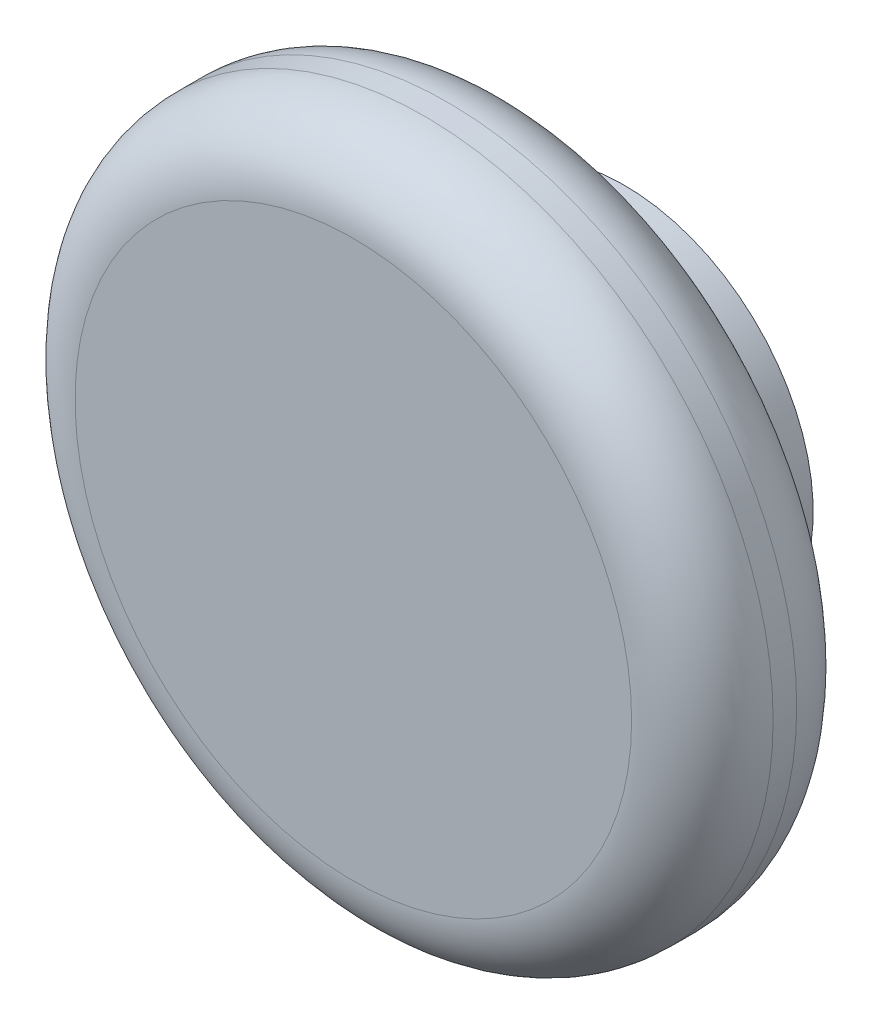
SolidWorks part; units mm, degrees
ref_plane "Front Plane" through (0, 0, 0) normal (0, 0, 1) x (1, 0, 0)
ref_plane "Top Plane" through (0, 0, 0) normal (0, 1, 0) x (1, 0, 0)
ref_plane "Right Plane" through (0, 0, 0) normal (1, 0, 0) x (0, 0, -1)
sketch "Sketch1" plane through (0, 0, 0) normal (0, 0, 1) x (1, 0, 0)
  circle A0 centre (-48.8952, 18.7018) radius 7.4
  dimension "D1" = 14.8
extrude "Boss-Extrude1" add sketch "Sketch1" along normal blind 3.5
sketch "Sketch2" plane through (0, 0, 0) normal (0, 0, -1) x (-1, 0, 0)
  circle A0 centre (48.8952, 18.7018) radius 4
  circle A1 centre (48.8952, 18.7018) radius 7.4 construction
  dimension "D1" = 0
extrude "Boss-Extrude2" add sketch "Sketch2" along normal blind 2.25 contours A0
fillet "Fillet1" radius 1.5 1 edges at (-41.4952, 18.7018, 3.5)
fillet "Fillet2" radius 1.5 1 edges at (-41.4952, 18.7018, 0)
